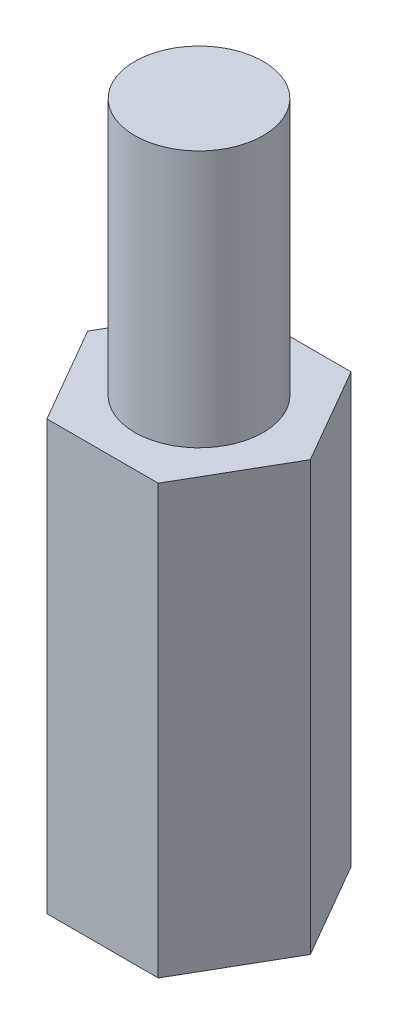
SolidWorks part; units mm, degrees
material "Commercial Bronze, UNS C22000 (90-10 Bronze)"
ref_plane "Front Plane" through (0, 0, 0) normal (0, 0, 1) x (1, 0, 0)
ref_plane "Top Plane" through (0, 0, 0) normal (0, 1, 0) x (1, 0, 0)
ref_plane "Right Plane" through (0, 0, 0) normal (1, 0, 0) x (0, 0, -1)
sketch "Sketch1" plane through (0, 0, 0) normal (0, 1, 0) x (1, 0, 0)
  line L1 (2.5981, 0) -> (1.299, 2.25)
  line L2 (1.299, 2.25) -> (-1.299, 2.25)
  line L3 (-1.299, 2.25) -> (-2.5981, 0)
  line L4 (-2.5981, 0) -> (-1.299, -2.25)
  line L5 (-1.299, -2.25) -> (1.299, -2.25)
  line L6 (1.299, -2.25) -> (2.5981, 0)
  circle A0 centre (0, 0) radius 2.25 construction
  circle A1 centre (0, 0) radius 1.5
  dimension "D1" = 4.5
  dimension "D2" = 3
extrude "Boss-Extrude1" add sketch "Sketch1" along normal blind 10
sketch "Sketch2" plane through (0, 10, 0) normal (0, 1, 0) x (1, 0, 0)
  line L1 (2.5981, 0) -> (1.299, 2.25)
  line L2 (1.299, 2.25) -> (-1.299, 2.25)
  line L3 (-1.299, 2.25) -> (-2.5981, 0)
  line L4 (-2.5981, 0) -> (-1.299, -2.25)
  line L5 (-1.299, -2.25) -> (1.299, -2.25)
  line L6 (1.299, -2.25) -> (2.5981, 0)
  circle A0 centre (0, 0) radius 2.25 construction
extrude "Boss-Extrude2" add sketch "Sketch2" against normal blind 3
sketch "Sketch3" plane through (0, 10, 0) normal (0, 1, 0) x (1, 0, 0)
  circle A0 centre (0, 0) radius 1.5
  dimension "D1" = 3
extrude "Boss-Extrude3" add sketch "Sketch3" along normal blind 6
